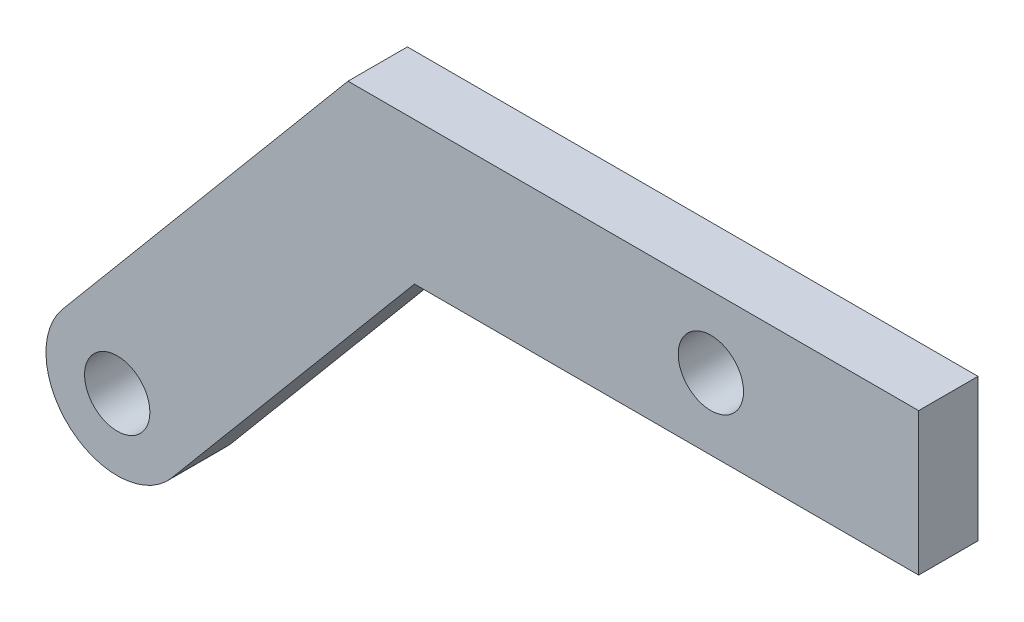
SolidWorks part; units mm, degrees
ref_plane "Płaszczyzna przednia" through (0, 0, 0) normal (0, 0, 1) x (1, 0, 0)
ref_plane "Płaszczyzna górna" through (0, 0, 0) normal (0, 1, 0) x (1, 0, 0)
ref_plane "Płaszczyzna prawa" through (0, 0, 0) normal (1, 0, 0) x (0, 0, -1)
sketch "Szkic1" plane through (0, 0, 0) normal (0, 0, 1) x (1, 0, 0)
  line L0 (38.8766, 65) -> (-9.1925, 7.7135)
  line L1 (9.1925, -7.7135) -> (50.068, 41)
  line L2 (50.068, 41) -> (135, 41)
  line L3 (135, 41) -> (135, 65)
  line L4 (135, 65) -> (38.8766, 65)
  line L5 (0, 0) -> (31.8799, 0) construction
  circle A0 centre (0, 0) radius 5.5
  arc A1 (-9.1925, 7.7135) -> (9.1925, -7.7135) centre (0, 0) ccw
  circle A2 centre (100, 53) radius 5.5
  dimension "D3" = 12
  dimension "D4" = 11
  dimension "D9" = 11
  dimension "D1" = 24
  dimension "D2" = 65
  dimension "D5" = 135
  dimension "D6" = 50
  dimension "D7" = 35
  dimension "D8" = 12
extrude "Dodanie-wyciągnięcie1" add sketch "Szkic1" along normal blind 10
